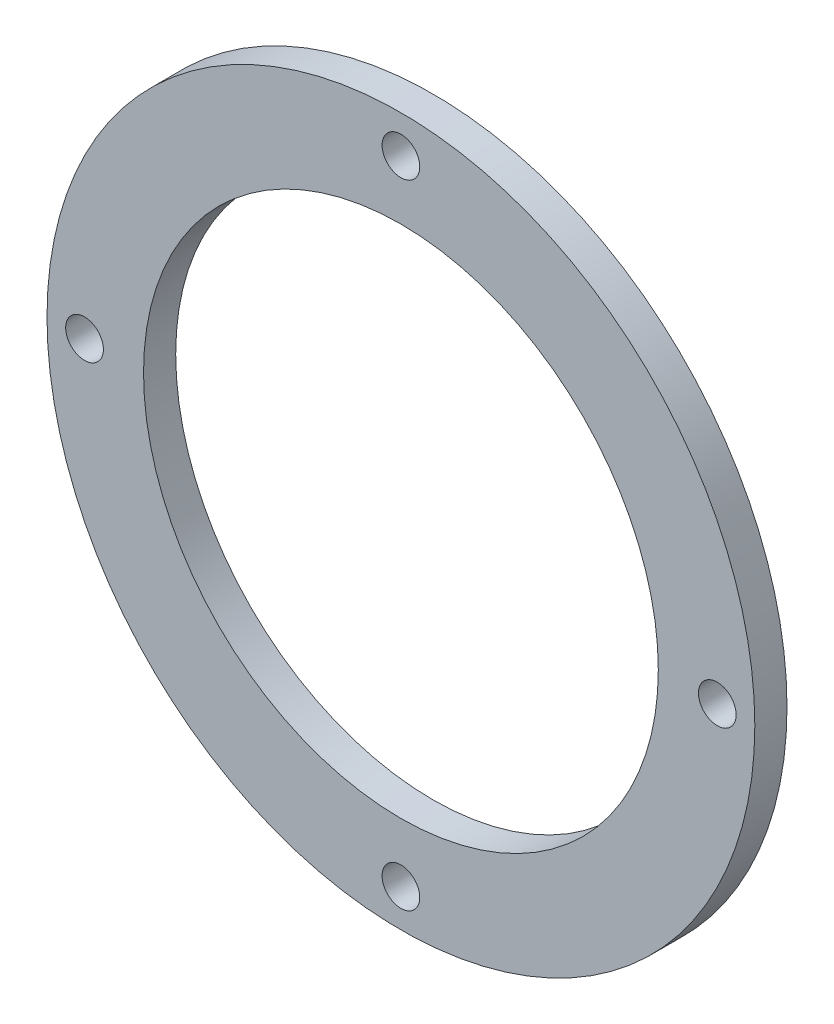
SolidWorks part; units mm, degrees
ref_plane "Front Plane" through (0, 0, 0) normal (0, 0, 1) x (1, 0, 0)
ref_plane "Top Plane" through (0, 0, 0) normal (0, 1, 0) x (1, 0, 0)
ref_plane "Right Plane" through (0, 0, 0) normal (1, 0, 0) x (0, 0, -1)
sketch "Sketch1" plane through (0, 0, 0) normal (0, 0, 1) x (1, 0, 0)
  circle A0 centre (0, 0) radius 24
  circle A1 centre (0, 0) radius 33
  circle A2 centre (0, 29.5) radius 1.7572
  circle A3 centre (29.5, 0) radius 1.7572
  circle A4 centre (0, -29.5) radius 1.7572
  circle A5 centre (-29.5, 0) radius 1.7572
  point P15 (0, 0)
  dimension "D1" = 66
  dimension "D2" = 48
  dimension "D3" = 29.5
  dimension "D4" = 4
extrude "Boss-Extrude1" add sketch "Sketch1" along normal blind 3
